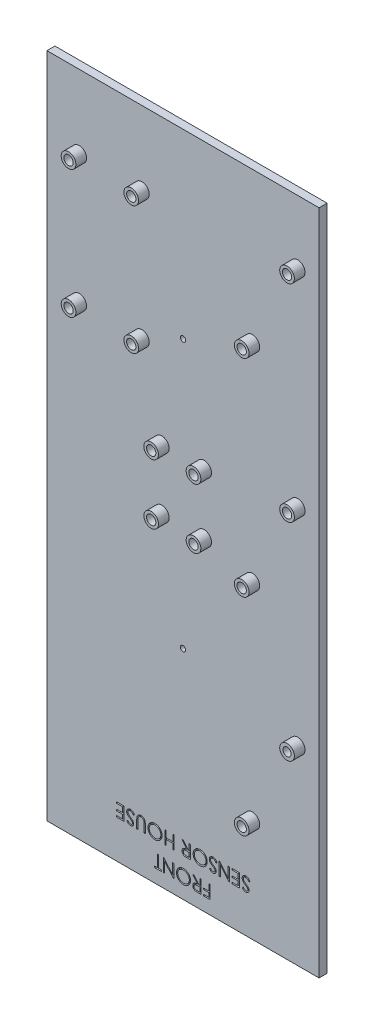
SolidWorks part; units mm, degrees
ref_plane "Front Plane" through (0, 0, 0) normal (1, 0, 0) x (0, 1, 0)
ref_plane "Top Plane" through (0, 0, 0) normal (0, 0, 1) x (0, 1, 0)
ref_plane "Right Plane" through (0, 0, 0) normal (0, 1, 0) x (-1, 0, 0)
sketch "Sketch1" plane through (0, 0, 0) normal (0, 0, 1) x (0, 1, 0)
  line L0 (132.5, 118) -> (132.5, 110) construction
  line L1 (0, 0) -> (265, 0) construction
  line L2 (0, 0) -> (0, 118) construction
  line L3 (0, 118) -> (265, 118) construction
  line L4 (265, 0) -> (265, 118) construction
  line L5 (132.5, 0) -> (132.5, 8) construction
  line L6 (0, 8) -> (265, 8) construction
  line L7 (0, 110) -> (171.25, 110) construction
  line L8 (0, 110) -> (0, 8) construction
  line L9 (265, 110) -> (265, 8) construction
  line L10 (265, 59) -> (250, 59) construction
  line L11 (250, 8) -> (250, 110) construction
  line L12 (0, 110) -> (0, 8)
  line L13 (250, 110) -> (199.75, 110) construction
  line L14 (250, 110) -> (250, 8) construction
  line L15 (250, 8) -> (0, 8) construction
  line L16 (0, 110) -> (0, 8) construction
  line L21 (250, 110) -> (225, 110) construction
  line L22 (250, 110) -> (250, 85) construction
  line L25 (0, 8) -> (250, 8)
  line L26 (250, 8) -> (250, 85)
  line L30 (225, 103.5715) -> (199.75, 103.5715) construction
  line L31 (199.75, 103.5715) -> (171.25, 103.5715) construction
  line L32 (199.75, 103.5715) -> (199.75, 118) construction
  line L33 (171.25, 103.5715) -> (171.25, 118) construction
  line L34 (171.25, 110) -> (0, 110)
  line L35 (199.75, 110) -> (265, 110) construction
  line L36 (171.25, 110) -> (0, 110) construction
  line L44 (199.75, 110) -> (225, 110)
  line L45 (171.25, 110) -> (199.75, 110)
  line L46 (225, 110) -> (250, 110)
  line L47 (250, 110) -> (250, 85)
  point P12 (132.5, 8)
  point P15 (132.5, 110)
  point P20 (250, 59)
  point P26 (171.25, 110)
extrude "Boss-Extrude1" add sketch "Sketch1" along normal blind 3
sketch "Sketch2" plane through (0, 0, 3) normal (0, 0, 1) x (1, 0, 0)
  line L2 (-59, 0) -> (-59, 81.4) construction
  line L8 (-59, 265) -> (-59, 181.94) construction
  circle A0 centre (-59, 81.4) radius 1
  circle A1 centre (-59, 181.94) radius 1
extrude "Cut-Extrude1" cut sketch "Sketch2" against normal blind 3
sketch "Sensor Layout" plane through (0, 0, 3) normal (0, 0, 1) x (1, 0, 0)
  line L0 (-110, 265) -> (-8, 0) construction
  line L1 (-8, 265) -> (-110, 0) construction
  line L2 (-59, 132.5) -> (-59, 146) construction
  line L3 (-59, 132.5) -> (-59, 119) construction
  line L4 (-59, 146) -> (-69, 146) construction
  line L5 (-59, 119) -> (-49, 119) construction
  line L6 (-69, 146) -> (-66.9344, 146) construction
  line L7 (-69, 146) -> (-49, 146) construction
  line L8 (-69, 146) -> (-69, 119) construction
  line L9 (-69, 119) -> (-49, 119) construction
  line L10 (-49, 146) -> (-49, 119) construction
  line L15 (-69, 143.75) -> (-66.9344, 143.75) construction
  line L16 (-66.9344, 146) -> (-66.9344, 143.75) construction
  line L17 (-69, 146) -> (-69, 143.75) construction
  line L18 (-49, 146) -> (-49, 143.75) construction
  line L19 (-51.0656, 146) -> (-51.0656, 143.75) construction
  line L20 (-51.0656, 146) -> (-49, 146) construction
  line L21 (-51.0656, 143.75) -> (-49, 143.75) construction
  line L22 (-69, 121.25) -> (-69, 119) construction
  line L23 (-69, 121.25) -> (-66.9344, 121.25) construction
  line L24 (-66.9344, 121.25) -> (-66.9344, 119) construction
  line L25 (-69, 119) -> (-66.9344, 119) construction
  line L26 (-51.0656, 119) -> (-49, 119) construction
  line L27 (-49, 121.25) -> (-49, 119) construction
  line L28 (-51.0656, 121.25) -> (-51.0656, 119) construction
  line L29 (-51.0656, 121.25) -> (-49, 121.25) construction
  line L30 (-49, 132.5) -> (-8, 132.5) construction
  line L31 (-86.1427, 198.5) -> (-86.1427, 132.5) construction
  line L32 (-24.5, 110.1219) -> (-24.5, 55.0212) construction
  line L33 (-24.5, 154.8781) -> (-24.5, 209.9788) construction
  line L34 (-35, 32.6431) -> (-14, 32.6431) construction
  line L35 (-35, 110.1219) -> (-14, 110.1219) construction
  line L36 (-35, 110.1219) -> (-35, 154.8781) construction
  line L37 (-35, 154.8781) -> (-14, 154.8781) construction
  line L38 (-14, 110.1219) -> (-14, 154.8781) construction
  line L39 (-35, 110.1219) -> (-14, 154.8781) construction
  line L40 (-35, 154.8781) -> (-14, 110.1219) construction
  line L45 (-35, 77.3993) -> (-14, 77.3993) construction
  line L46 (-14, 32.6431) -> (-14, 77.3993) construction
  line L47 (-35, 32.6431) -> (-35, 77.3993) construction
  line L48 (-35, 187.6007) -> (-35, 232.3569) construction
  line L49 (-35, 232.3569) -> (-14, 232.3569) construction
  line L50 (-14, 187.6007) -> (-14, 232.3569) construction
  line L51 (-35, 187.6007) -> (-14, 187.6007) construction
  line L64 (-16, 232.3569) -> (-16, 226.3569) construction
  line L65 (-16, 226.3569) -> (-14, 226.3569) construction
  line L66 (-14, 232.3569) -> (-14, 226.3569) construction
  line L67 (-16, 232.3569) -> (-14, 232.3569) construction
  line L68 (-16, 154.8781) -> (-16, 148.8781) construction
  line L69 (-14, 154.8781) -> (-14, 148.8781) construction
  line L70 (-16, 148.8781) -> (-14, 148.8781) construction
  line L71 (-16, 154.8781) -> (-14, 154.8781) construction
  line L72 (-16, 77.3993) -> (-14, 77.3993) construction
  line L73 (-16, 77.3993) -> (-16, 71.3993) construction
  line L74 (-16, 71.3993) -> (-14, 71.3993) construction
  line L75 (-14, 77.3993) -> (-14, 71.3993) construction
  line L88 (-35, 193.6007) -> (-35, 187.6007) construction
  line L89 (-35, 187.6007) -> (-33, 187.6007) construction
  line L90 (-33, 193.6007) -> (-33, 187.6007) construction
  line L91 (-35, 193.6007) -> (-33, 193.6007) construction
  line L92 (-35, 116.1219) -> (-35, 110.1219) construction
  line L93 (-35, 116.1219) -> (-33, 116.1219) construction
  line L94 (-33, 116.1219) -> (-33, 110.1219) construction
  line L95 (-35, 110.1219) -> (-33, 110.1219) construction
  line L96 (-35, 32.6431) -> (-33, 32.6431) construction
  line L97 (-33, 38.6431) -> (-33, 32.6431) construction
  line L98 (-35, 38.6431) -> (-33, 38.6431) construction
  line L99 (-35, 38.6431) -> (-35, 32.6431) construction
  line L100 (-69, 132.5) -> (-110, 132.5) construction
  line L124 (-62.2853, 146) -> (-62.2853, 225) construction
  line L126 (-100.3927, 222.5) -> (-100.3927, 225) construction
  line L127 (-110, 265) -> (-8, 265) construction
  line L128 (-110, 265) -> (-110, 0) construction
  line L129 (-110, 0) -> (-8, 0) construction
  line L130 (-8, 265) -> (-8, 0) construction
  line L131 (-71.8927, 172) -> (-100.3927, 172) construction
  line L132 (-71.8927, 225) -> (-74.3927, 225) construction
  line L133 (-100.3927, 225) -> (-100.3927, 172) construction
  line L134 (-71.8927, 172) -> (-71.8927, 174.5) construction
  line L135 (-121.574, 269.905) -> (3.81, 269.905) construction
  line L136 (-121.574, 269.905) -> (-121.574, -7.14) construction
  line L137 (-121.574, -7.14) -> (3.81, -7.14) construction
  line L138 (3.81, 269.905) -> (3.81, -7.14) construction
  line L139 (-74.3927, 222.5) -> (-74.3927, 225) construction
  line L140 (-71.8927, 225) -> (-100.3927, 172) construction
  line L141 (-97.8927, 222.5) -> (-97.8927, 225) construction
  line L142 (-97.8927, 174.5) -> (-100.3927, 174.5) construction
  line L143 (-100.3927, 172) -> (-100.3927, 174.5) construction
  line L144 (-71.8927, 172) -> (-100.3927, 225) construction
  line L145 (-97.8927, 222.5) -> (-100.3927, 222.5) construction
  line L146 (-71.8927, 225) -> (-100.3927, 225) construction
  line L147 (-71.8927, 172) -> (-74.3927, 172) construction
  line L148 (-71.8927, 222.5) -> (-71.8927, 225) construction
  line L149 (-71.8927, 225) -> (-71.8927, 172) construction
  line L150 (-71.8927, 222.5) -> (-74.3927, 222.5) construction
  line L151 (-71.8927, 174.5) -> (-74.3927, 174.5) construction
  line L152 (-74.3927, 172) -> (-74.3927, 174.5) construction
  line L153 (-97.8927, 172) -> (-100.3927, 172) construction
  line L154 (-97.8927, 225) -> (-100.3927, 225) construction
  line L155 (-97.8927, 172) -> (-97.8927, 174.5) construction
  point P35 (-24.5, 132.5)
  point P40 (-24.5, 132.5)
sketch "Sketch5" plane through (0, 0, 3) normal (0, 0, 1) x (1, 0, 0)
  circle A4 centre (-66.9344, 143.75) radius 2.75
  circle A5 centre (-51.0656, 143.75) radius 2.75
  circle A6 centre (-66.9344, 121.25) radius 2.75
  circle A7 centre (-51.0656, 121.25) radius 2.75
  circle A8 centre (-16, 148.8781) radius 2.75
  circle A9 centre (-33, 116.1219) radius 2.75
  circle A10 centre (-16, 71.3993) radius 2.75
  circle A11 centre (-33, 38.6431) radius 2.75
  circle A12 centre (-16, 226.3569) radius 2.75
  circle A13 centre (-33, 193.6007) radius 2.75
  circle A14 centre (-97.8927, 222.5) radius 2.75
  circle A15 centre (-74.3927, 222.5) radius 2.75
  circle A16 centre (-74.3927, 174.5) radius 2.75
  circle A17 centre (-97.8927, 174.5) radius 2.75
extrude "Boss-Extrude2" add sketch "Sketch5" along normal blind 4
sketch "Sketch6" plane through (0, 0, 3) normal (0, 0, 1) x (1, 0, 0)
  circle A4 centre (-66.9344, 143.75) radius 1.75
  circle A5 centre (-51.0656, 143.75) radius 1.75
  circle A6 centre (-66.9344, 121.25) radius 1.75
  circle A7 centre (-51.0656, 121.25) radius 1.75
  circle A8 centre (-33, 116.1219) radius 1.75
  circle A9 centre (-16, 148.8781) radius 1.75
  circle A10 centre (-16, 71.3993) radius 1.5412
  circle A11 centre (-33, 38.6431) radius 1.75
  circle A12 centre (-16, 226.3569) radius 1.75
  circle A13 centre (-33, 193.6007) radius 1.75
  circle A14 centre (-97.8927, 222.5) radius 1.75
  circle A15 centre (-74.3927, 222.5) radius 1.75
  circle A16 centre (-74.3927, 174.5) radius 1.75
  circle A17 centre (-97.8927, 174.5) radius 1.75
extrude "Cut-Extrude2" cut sketch "Sketch6" along normal blind 4
sketch "Sketch7" plane through (0, 0, 3) normal (0, 0, 1) x (1, 0, 0)
  line L0 (-59, 0) -> (-59, 10) construction
  line L2 (-9, 10) -> (-109, 10) construction
  text T0 "FRONT\r\nSENSOR HOUSE" font "Century Gothic" height 5
  point P7 (-59, 10)
extrude "Cut-Extrude3" cut sketch "Sketch7" against normal blind 1
